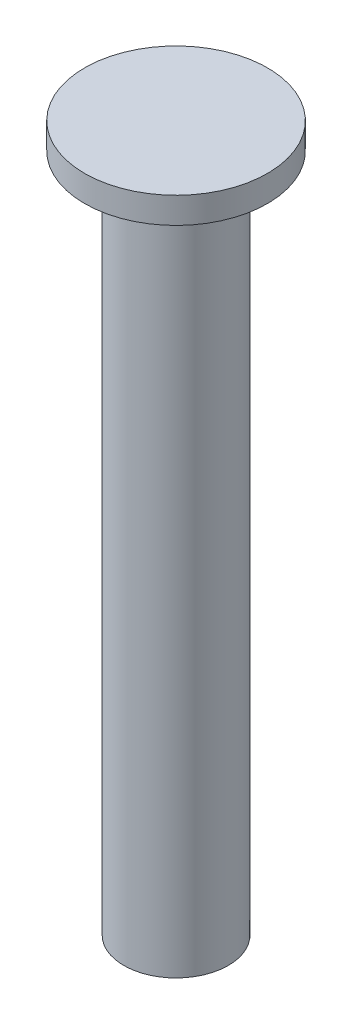
SolidWorks part; units mm, degrees
ref_plane "Front Plane" through (0, 0, 0) normal (0, 0, 1) x (1, 0, 0)
ref_plane "Top Plane" through (0, 0, 0) normal (0, 1, 0) x (1, 0, 0)
ref_plane "Right Plane" through (0, 0, 0) normal (1, 0, 0) x (0, 0, -1)
sketch "Sketch1" plane through (0, 0, 0) normal (0, 1, 0) x (1, 0, 0)
  circle A0 centre (0, 0) radius 2
  dimension "D1" = 4
extrude "Boss-Extrude1" add sketch "Sketch1" along normal blind 26
sketch "Sketch2" plane through (0, 26, 0) normal (0, 1, 0) x (1, 0, 0)
  circle A0 centre (0, 0) radius 3.5
  dimension "D1" = 7
extrude "Boss-Extrude2" add sketch "Sketch2" along normal blind 1
